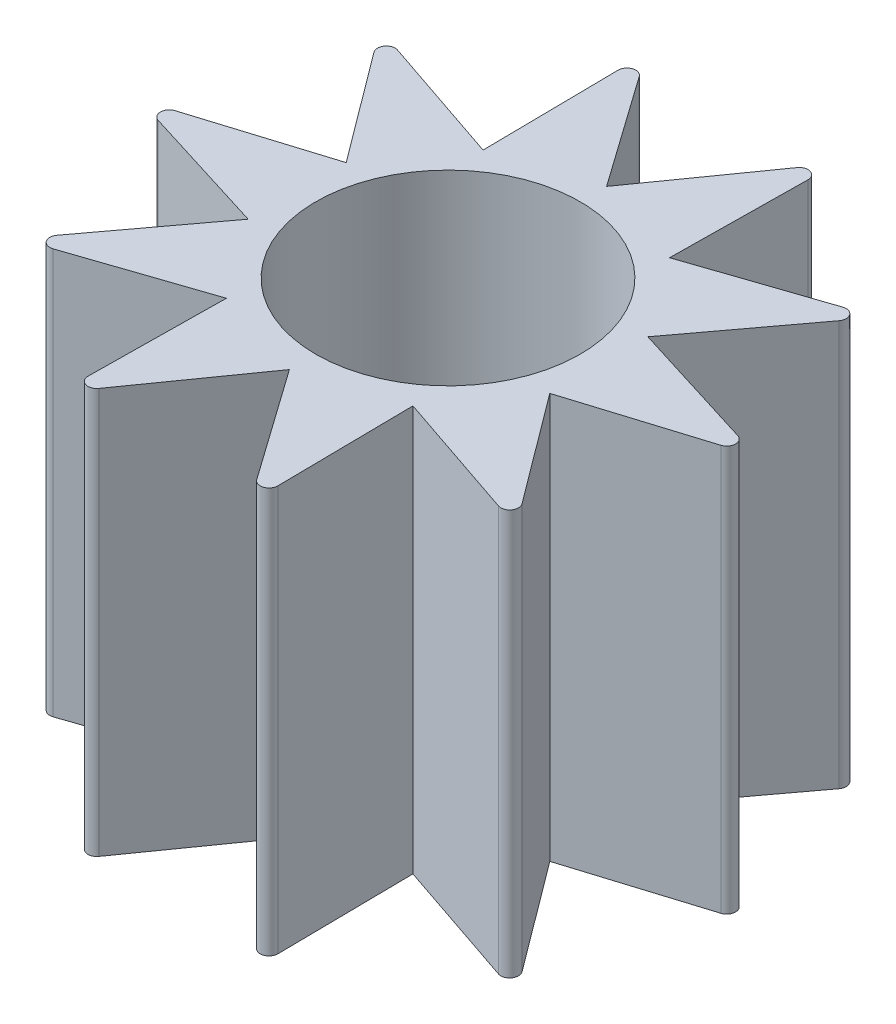
SolidWorks part; units mm, degrees
ref_plane "前基準面" through (0, 0, 0) normal (0, 0, 1) x (1, 0, 0)
ref_plane "上基準面" through (0, 0, 0) normal (0, 1, 0) x (1, 0, 0)
ref_plane "右基準面" through (0, 0, 0) normal (1, 0, 0) x (0, 0, -1)
sketch "草圖1" plane through (0, 0, 0) normal (0, 1, 0) x (1, 0, 0)
  circle A0 centre (0, 0) radius 1.75
  dimension "D1" = 3.5
extrude "伸長1" add sketch "草圖1" along normal blind 2.3
sketch "草圖2" plane through (0, 2.3, 0) normal (0, 1, 0) x (1, 0, 0)
  line L0 (0, 0) -> (0, 0.9) construction
  line L1 (0, 0) -> (0.529, 0.7281) construction
  line L2 (0.529, 0.7281) -> (0.5388, 1.5036)
  line L3 (0.4479, 1.5331) -> (0, 0.9)
  line L4 (1.2635, 0.977) -> (0.529, 0.7281)
  line L5 (0.856, 0.2781) -> (1.3197, 0.8998)
  line L6 (1.5965, 0.0477) -> (0.856, 0.2781)
  line L7 (0, 0) -> (0.5408, 1.6643) construction
  line L8 (0.856, -0.2781) -> (1.5965, -0.0477)
  line L9 (1.3197, -0.8998) -> (0.856, -0.2781)
  line L10 (0.529, -0.7281) -> (1.2635, -0.977)
  line L11 (0.5388, -1.5036) -> (0.529, -0.7281)
  line L12 (0, -0.9) -> (0.4479, -1.5331)
  line L13 (-0.4479, -1.5331) -> (0, -0.9)
  line L14 (-0.529, -0.7281) -> (-0.5388, -1.5036)
  line L15 (-1.2635, -0.977) -> (-0.529, -0.7281)
  line L16 (-0.856, -0.2781) -> (-1.3197, -0.8998)
  line L17 (-1.5965, -0.0477) -> (-0.856, -0.2781)
  line L18 (-0.856, 0.2781) -> (-1.5965, 0.0477)
  line L19 (-1.3197, 0.8998) -> (-0.856, 0.2781)
  line L20 (-0.529, 0.7281) -> (-1.2635, 0.977)
  line L21 (-0.5388, 1.5036) -> (-0.529, 0.7281)
  line L22 (0, 0.9) -> (-0.4479, 1.5331)
  circle A0 centre (0, 0) radius 0.75
  circle A1 centre (0, 0) radius 1.75 construction
  circle A2 centre (0, 0) radius 0.9 construction
  arc A3 (0.5388, 1.5036) -> (0.4479, 1.5331) centre (0.4888, 1.5043) ccw
  arc A4 (1.3197, 0.8998) -> (1.2635, 0.977) centre (1.2796, 0.9297) ccw
  arc A5 (1.5965, -0.0477) -> (1.5965, 0.0477) centre (1.5817, 0) ccw
  arc A6 (1.2635, -0.977) -> (1.3197, -0.8998) centre (1.2796, -0.9297) ccw
  arc A7 (0.4479, -1.5331) -> (0.5388, -1.5036) centre (0.4888, -1.5043) ccw
  arc A8 (-0.5388, -1.5036) -> (-0.4479, -1.5331) centre (-0.4888, -1.5043) ccw
  arc A9 (-1.3197, -0.8998) -> (-1.2635, -0.977) centre (-1.2796, -0.9297) ccw
  arc A10 (-1.5965, 0.0477) -> (-1.5965, -0.0477) centre (-1.5817, 0) ccw
  arc A11 (-1.2635, 0.977) -> (-1.3197, 0.8998) centre (-1.2796, 0.9297) ccw
  arc A12 (-0.4479, 1.5331) -> (-0.5388, 1.5036) centre (-0.4888, 1.5043) ccw
  dimension "D1" = 1.5
  dimension "D4" = 1.8
  dimension "D5" = 0.05
  dimension "D2" = 36
  dimension "D3" = 18
extrude "伸長2" cut sketch "草圖2" against normal up to next (2.3 mm away) flip side to cut
